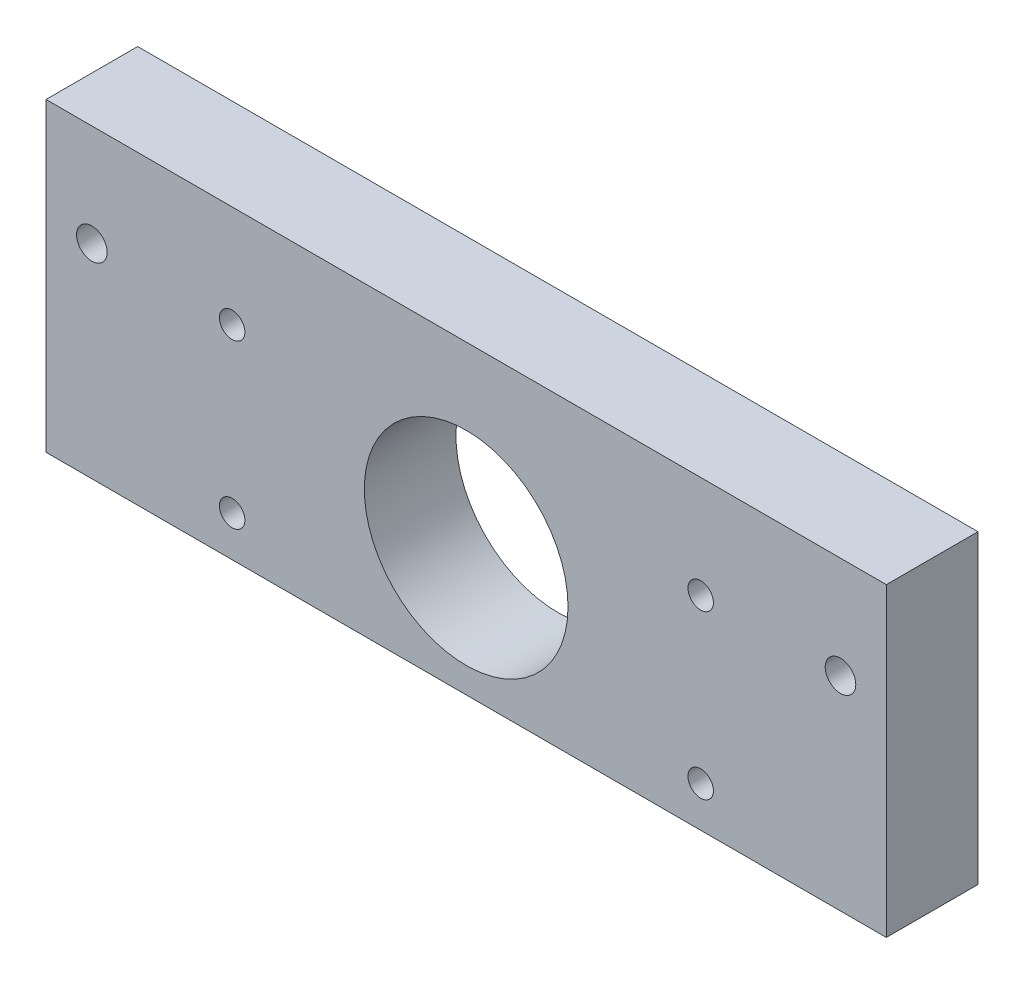
SolidWorks part; units mm, degrees
ref_plane "Front Plane" through (0, 0, 0) normal (0, 0, 1) x (1, 0, 0)
ref_plane "Top Plane" through (0, 0, 0) normal (0, 1, 0) x (1, 0, 0)
ref_plane "Right Plane" through (0, 0, 0) normal (1, 0, 0) x (0, 0, -1)
sketch "Sketch1" plane through (0, 0, 0) normal (0, 0, 1) x (1, 0, 0)
  line L1 (-82.5, 30) -> (82.5, 30)
  line L2 (-82.5, 30) -> (-82.5, -30)
  line L3 (-82.5, -30) -> (82.5, -30)
  line L4 (82.5, 30) -> (82.5, -30)
  line L5 (-82.5, 30) -> (82.5, -30) construction
  line L6 (-82.5, -30) -> (82.5, 30) construction
  point P0 (0, 0)
  dimension "D1" = 165
  dimension "D2" = 60
extrude "Boss-Extrude1" add sketch "Sketch1" along normal blind 18
sketch "Sketch3" plane through (0, 0, 18) normal (0, 0, 1) x (1, 0, 0)
  line L0 (-82.5, -30) -> (82.5, -30) construction
  circle A0 centre (0, -5) radius 20
  dimension "D1" = 40
  dimension "D2" = 25
extrude "Cut-Extrude2" cut sketch "Sketch3" against normal blind 18
hole_wizard "Ø4.0 (4) Diameter Hole1" positions "Sketch7" profile "Sketch6" hole size "Ø4.0" standard "ISO"
sketch "Sketch7" plane through (0, -30, 0) normal (0, -1, 0) x (-1, 0, 0)
  point P0 (57.5, -9)
  point P3 (-57.5, -9)
sketch "Sketch6" plane through (-57.5, -30, 9) normal (1, 0, 0) x (0, 0, -1)
  line L0 (0, 0) -> (0, 31.2017)
  line L1 (0, 31.2017) -> (2, 30)
  line L2 (2, 30) -> (2, 0)
  line L5 (2, 0) -> (0, 0)
  line L10 (0, 31.2017) -> (-2, 30) construction
  line L11 (0, -6.35) -> (0, 107.95) construction
  dimension "Hole Dia." = 4
  dimension "Hole Depth" = 30
  dimension "Drill Angle" = 118
hole_wizard "Ø6.0 (6) Diameter Hole2" positions "Sketch14" profile "Sketch13" hole size "Ø6.0" standard "ISO"
sketch "Sketch14" plane through (0, 0, 18) normal (0, 0, 1) x (1, 0, 0)
  line L0 (82.5, 30) -> (-82.5, 30) construction
  line L1 (82.5, -30) -> (82.5, 30) construction
  line L2 (-82.5, 30) -> (-82.5, -30) construction
  point P0 (73.5, 10)
  point P2 (-73.5, 10)
  dimension "D1" = 20
  dimension "D2" = 9
  dimension "D3" = 20
  dimension "D4" = 9
sketch "Sketch13" plane through (73.5, 10, 18) normal (1, 0, 0) x (0, -1, 0)
  line L0 (0, 0) -> (0, 14)
  line L1 (0, 14) -> (3, 14)
  line L2 (3, 14) -> (3, 0)
  line L5 (3, 0) -> (0, 0)
  line L10 (0, 14) -> (-3, 14) construction
  line L11 (0, -6.35) -> (0, 107.95) construction
  dimension "Hole Dia." = 6
  dimension "Hole Depth" = 14
  dimension "Drill Angle" = 180
hole_wizard "Ø5.0 (5) Diameter Hole1" positions "Sketch16" profile "Sketch15" hole size "Ø5.0" standard "ISO" end condition through all
sketch "Sketch16" plane through (0, 0, 0) normal (0, 0, -1) x (-1, 0, 0)
  point P0 (-46.05, 9.95)
  point P2 (-46.05, -22.05)
  point P4 (45.95, 9.95)
  point P6 (45.95, -22.05)
sketch "Sketch15" plane through (46.05, 9.95, 0) normal (1, 0, 0) x (0, 1, 0)
  line L0 (0, 0) -> (0, 18)
  line L1 (0, 18) -> (2.5, 18)
  line L2 (2.5, 18) -> (2.5, 0)
  line L5 (2.5, 0) -> (0, 0)
  line L11 (0, -6.35) -> (0, 107.95) construction
  dimension "Thru Hole Dia." = 5
  dimension "Thru Hole Depth" = 18
